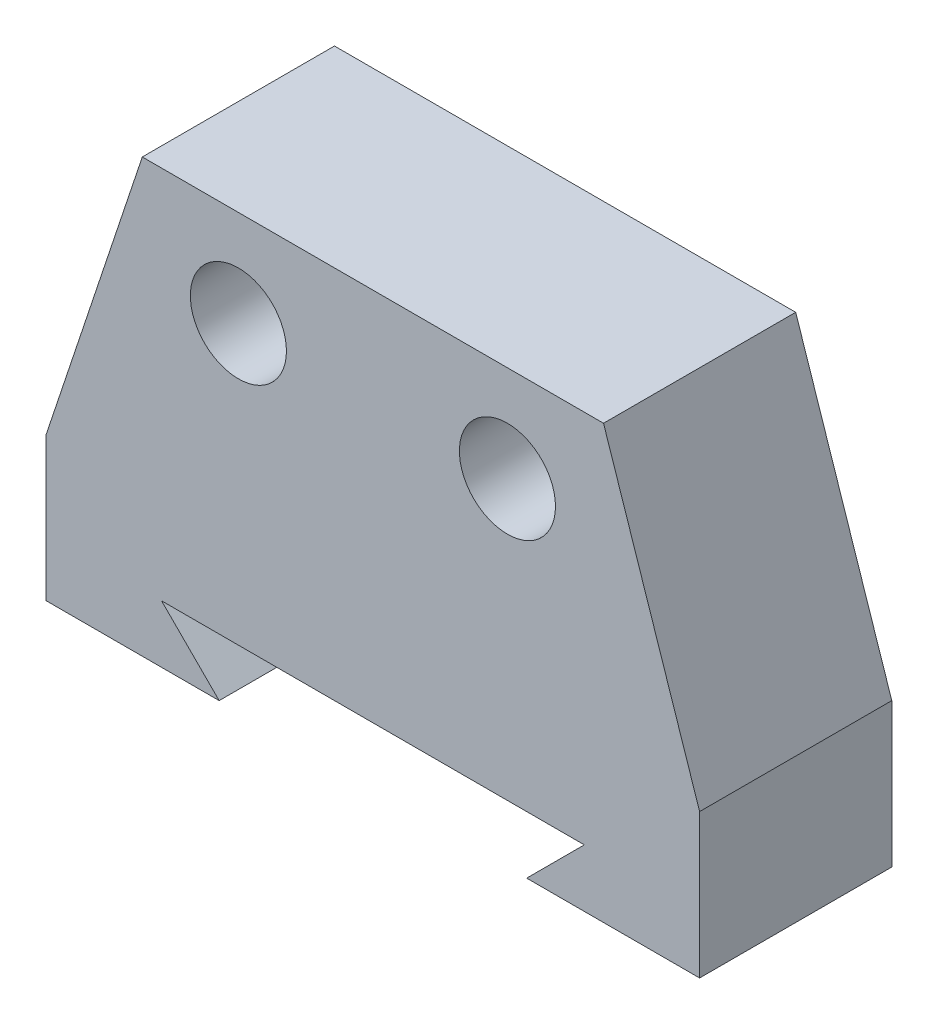
SolidWorks part; units mm, degrees
ref_plane "Front Plane" through (0, 0, 0) normal (0, 0, 1) x (1, 0, 0)
ref_plane "Top Plane" through (0, 0, 0) normal (0, 1, 0) x (1, 0, 0)
ref_plane "Right Plane" through (0, 0, 0) normal (1, 0, 0) x (0, 0, -1)
sketch "Sketch1" plane through (0, 0, 0) normal (0, 0, 1) x (1, 0, 0)
  line L0 (0, 0) -> (0, -50000) construction
  line L1 (0, 0) -> (-50000, 0) construction
  line L2 (-24, 39) -> (24, 39)
  line L3 (24, 39) -> (34, 9)
  line L4 (34, 9) -> (34, 0)
  line L5 (22, 0) -> (16, -6)
  line L6 (16, -6) -> (34, -6)
  line L7 (34, -6) -> (34, 0)
  line L8 (-22, 0) -> (22, 0)
  line L9 (-34, -6) -> (-34, 0)
  line L10 (-16, -6) -> (-34, -6)
  line L11 (-22, 0) -> (-16, -6)
  line L12 (-34, 9) -> (-34, 0)
  line L13 (-24, 39) -> (-34, 9)
  line L14 (24, 39) -> (34, 9)
  line L15 (34, 9) -> (34, 0)
  line L16 (22, 0) -> (16, -6)
  line L17 (16, -6) -> (34, -6)
  line L18 (34, -6) -> (34, 0)
  circle A0 centre (-14, 29) radius 5
  circle A1 centre (14, 29) radius 5
  point P14 (0, 0)
  point P19 (0, 39)
  dimension "D7" = 10
  dimension "D1" = 45
  dimension "D2" = 6
  dimension "D3" = 48
  dimension "D4" = 45
  dimension "D5" = 68
  dimension "D6" = 15
  dimension "D8" = 20
  dimension "D9" = 35
  dimension "D10" = 18
extrude "Boss-Extrude1" add sketch "Sketch1" along normal mid plane 20 contours L2 L13 L12 L9 L10 L11 L8 L5 L6 L7 L4 L3 A0 A1
